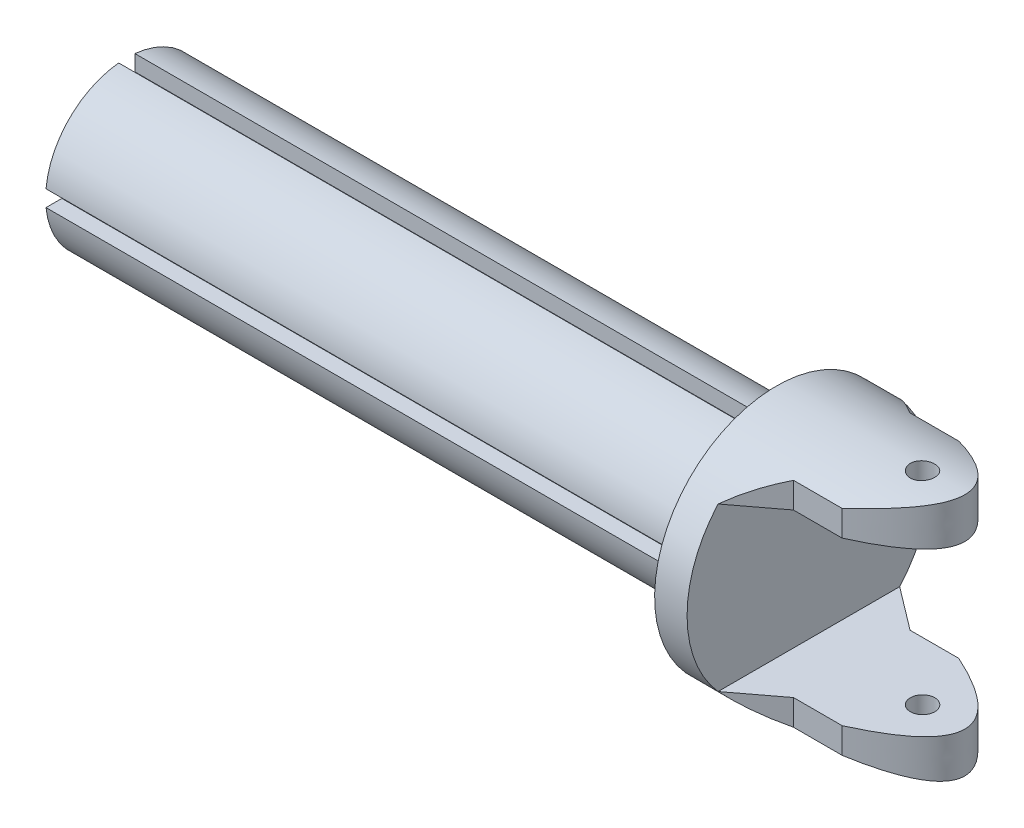
SolidWorks part; units mm, degrees
ref_plane "Front Plane" through (0, 0, 0) normal (0, 0, 1) x (1, 0, 0)
ref_plane "Top Plane" through (0, 0, 0) normal (0, 1, 0) x (1, 0, 0)
ref_plane "Right Plane" through (0, 0, 0) normal (1, 0, 0) x (0, 0, -1)
sketch "Sketch1" plane through (0, 0, 0) normal (1, 0, 0) x (0, 0, -1)
  line L1 (-0.5, 4) -> (0.5, 4)
  line L2 (-0.5, 4) -> (-0.5, 4.9749)
  line L4 (0.5, 4) -> (0.5, 4.9749)
  line L5 (-0.5, 4) -> (0.5, 6) construction
  line L6 (-0.5, 6) -> (0.5, 4) construction
  line L7 (-0.5, -4) -> (0.5, -4)
  line L8 (-0.5, -4) -> (-0.5, -4.9749)
  line L10 (0.5, -4) -> (0.5, -4.9749)
  line L11 (-0.5, -4) -> (0.5, -6) construction
  line L12 (-0.5, -6) -> (0.5, -4) construction
  line L13 (4, -0.5) -> (4.9749, -0.5)
  line L14 (4, -0.5) -> (4, 0.5)
  line L15 (4, 0.5) -> (4.9749, 0.5)
  line L17 (4, -0.5) -> (6, 0.5) construction
  line L18 (4, 0.5) -> (6, -0.5) construction
  line L19 (-4, -0.5) -> (-4.9749, -0.5)
  line L20 (-4, -0.5) -> (-4, 0.5)
  line L21 (-4, 0.5) -> (-4.9749, 0.5)
  line L23 (-4, -0.5) -> (-6, 0.5) construction
  line L24 (-4, 0.5) -> (-6, -0.5) construction
  arc A0 (-4.9749, -0.5) -> (-0.5, -4.9749) centre (0, 0) ccw
  arc A1 (0.5, -4.9749) -> (4.9749, -0.5) centre (0, 0) ccw
  arc A2 (4.9749, 0.5) -> (0.5, 4.9749) centre (0, 0) ccw
  arc A3 (-0.5, 4.9749) -> (-4.9749, 0.5) centre (0, 0) ccw
  point P3 (0, 5)
  point P8 (0, -5)
  point P13 (5, 0)
  point P18 (-5, 0)
  dimension "D1" = 10
  dimension "D2" = 2
  dimension "D3" = 2
  dimension "D4" = 1
  dimension "D5" = 1
  dimension "D6" = 2
  dimension "D7" = 1
  dimension "D8" = 2
  dimension "D9" = 1
extrude "Boss-Extrude1" add sketch "Sketch1" along normal blind 40
sketch "Sketch2" plane through (40, 0, 0) normal (1, 0, 0) x (0, 0, -1)
  circle A0 centre (0, 0) radius 7.5
  dimension "D1" = 15
extrude "Boss-Extrude2" add sketch "Sketch2" along normal blind 2
sketch "Sketch3" plane through (42, 0, 0) normal (1, 0, 0) x (0, 0, -1)
  line L1 (-5.5902, -5) -> (5.5902, -5)
  line L2 (-5.5902, -5) -> (-5.5902, 5)
  line L3 (-5.5902, 5) -> (5.5902, 5)
  line L4 (5.5902, -5) -> (5.5902, 5)
  line L5 (-5.5902, -5) -> (5.5902, 5) construction
  line L6 (-5.5902, 5) -> (5.5902, -5) construction
  arc A0 (-4.899, 5) -> (-4.899, -5) centre (0, 0) ccw
  circle A1 centre (0, 0) radius 7.5 construction
  arc A2 (4.899, -5) -> (4.899, 5) centre (0, 0) ccw
  point P0 (0, 0)
  circle M2 centre (0, 0) radius 7.5
  dimension "D1" = 10
extrude "Boss-Extrude3" add sketch "Sketch3" along normal blind 10 contours L3 M2 | L1 M2
sketch "Sketch4" plane through (0, 5, 0) normal (0, -1, 0) x (1, 0, 0)
  line L0 (52, 0) -> (5.8747, 0) construction
  line L1 (52, 5.5902) -> (52, -5.5902) construction
  line L7 (42, 5.5902) -> (52, 5.5902)
  line L8 (52, 5.5902) -> (52, -5.5902)
  line L9 (52, -5.5902) -> (42, -5.5902)
  line L10 (42, 5.5902) -> (44.6404, 3.5902)
  line L11 (44.6404, 3.5902) -> (47.6404, 3.5902)
  line L12 (47.6404, -3.5902) -> (44.6404, -3.5902)
  line L13 (44.6404, -3.5902) -> (42, -5.5902)
  spline S0 degree 3 poles (47.6404, -3.5902) (50.2801, -2.3934) (52.9199, 0) (50.2801, 2.3934) (47.6404, 3.5902) knots 0.178885 0.178885 0.178885 0.178885 0.5 0.821115 0.821115 0.821115 0.821115
  dimension "D1" = 9.6
  dimension "D2" = 3
  dimension "D3" = 2
  dimension "D4" = 3
  dimension "D5" = 2
extrude "Cut-Extrude1" cut sketch "Sketch4" against normal through all both and the other way through all
sketch "Sketch5" plane through (0, 5, 0) normal (0, -1, 0) x (1, 0, 0)
  line L0 (42, 0) -> (17.8474, 0) construction
  line L1 (42, 5.5902) -> (42, -5.5902) construction
  circle A0 centre (49, 0) radius 0.75
  dimension "D2" = 1.5
  dimension "D1" = 7
extrude "Cut-Extrude2" cut sketch "Sketch5" against normal through all both and the other way through all
sketch "Sketch6" plane through (0, 0, 0) normal (-1, 0, 0) x (0, 0, 1)
  circle A0 centre (0, 0) radius 5
  dimension "D1" = 10
extrude "Cut-Extrude3" [suppressed] cut sketch "Sketch6" against normal blind 30
